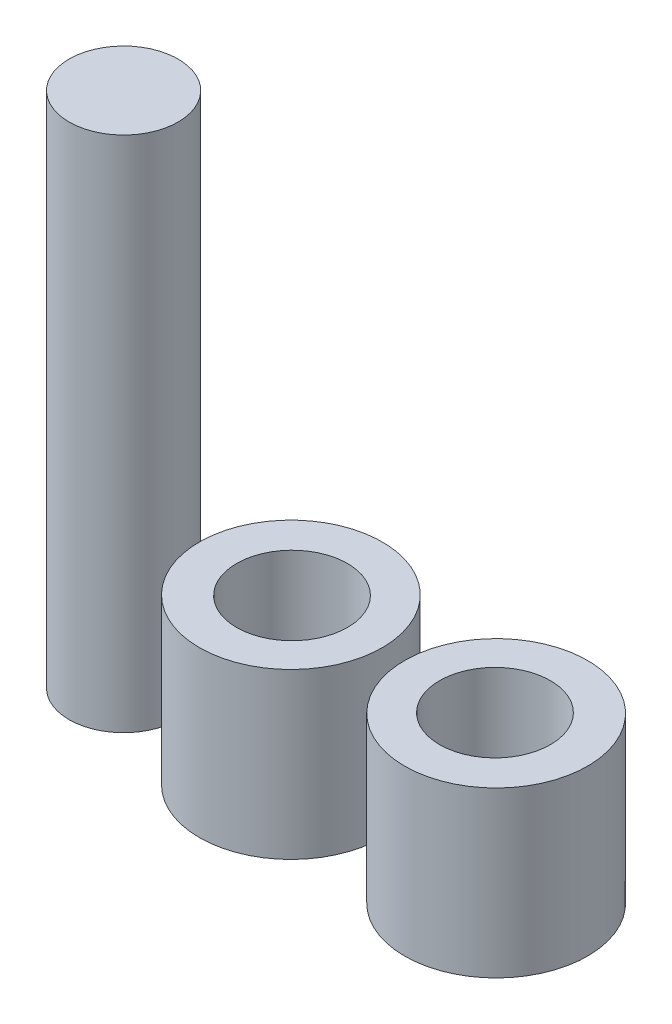
SolidWorks part; units mm, degrees
ref_plane "Front Plane" through (0, 0, 0) normal (0, 0, 1) x (1, 0, 0)
ref_plane "Top Plane" through (0, 0, 0) normal (0, 1, 0) x (1, 0, 0)
ref_plane "Right Plane" through (0, 0, 0) normal (1, 0, 0) x (0, 0, -1)
sketch "Sketch1" plane through (0, 0, 0) normal (0, 1, 0) x (1, 0, 0)
  line L0 (-3.5419, 0) -> (3.4353, 0) construction
  circle A0 centre (0, 0) radius 1.475
  dimension "D1" = 2.95
extrude "Boss-Extrude1" add sketch "Sketch1" along normal blind 14
sketch "Sketch2" plane through (0, 0, 0) normal (0, 1, 0) x (1, 0, 0)
  line L0 (-2.9584, 0) -> (3.1211, 0) construction
  line L1 (3.1211, 0) -> (7.9843, 0) construction
  circle A0 centre (4.5241, 0) radius 2.475
  dimension "D1" = 4.95
extrude "Boss-Extrude2" add sketch "Sketch2" along normal blind 4.45 contours A0
sketch "Sketch3" plane through (0, 4.45, 0) normal (0, 1, 0) x (1, 0, 0)
  line L0 (7.471, 0) -> (1.6396, 0) construction
  circle A0 centre (4.5553, 0) radius 1.5
  dimension "D1" = 3
extrude "Cut-Extrude1" cut sketch "Sketch3" against normal through all
ref_plane "Plane1" through (7.3, 0, 0) normal (1, 0, 0) x (0, 0, -1)
mirror "Mirror23" about plane through (7.3, 0, 0) normal (1, 0, 0) of bodies 103
